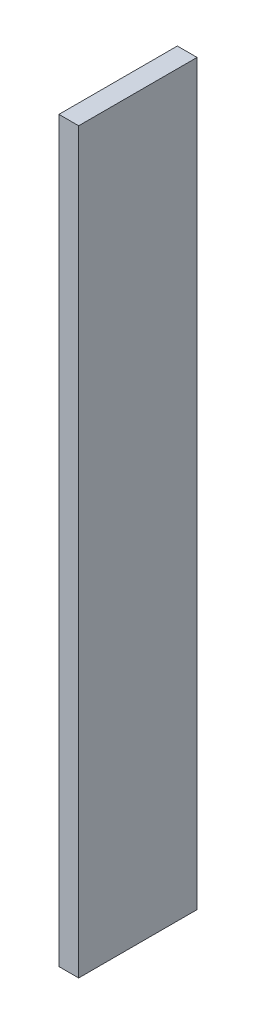
SolidWorks part; units mm, degrees
ref_plane "Спереди" through (0, 0, 0) normal (0, 0, 1) x (1, 0, 0)
ref_plane "Сверху" through (0, 0, 0) normal (0, 1, 0) x (1, 0, 0)
ref_plane "Справа" through (0, 0, 0) normal (1, 0, 0) x (0, 0, -1)
sketch "Эскиз1" plane through (0, 0, 0) normal (0, 1, 0) x (1, 0, 0)
  line L1 (0, 0) -> (5, 0)
  line L2 (0, 0) -> (0, -30)
  line L3 (0, -30) -> (5, -30)
  line L4 (5, 0) -> (5, -30)
  dimension "D1" = 5
  dimension "D2" = 30
extrude "Бобышка-Вытянуть1" add sketch "Эскиз1" along normal blind 187
